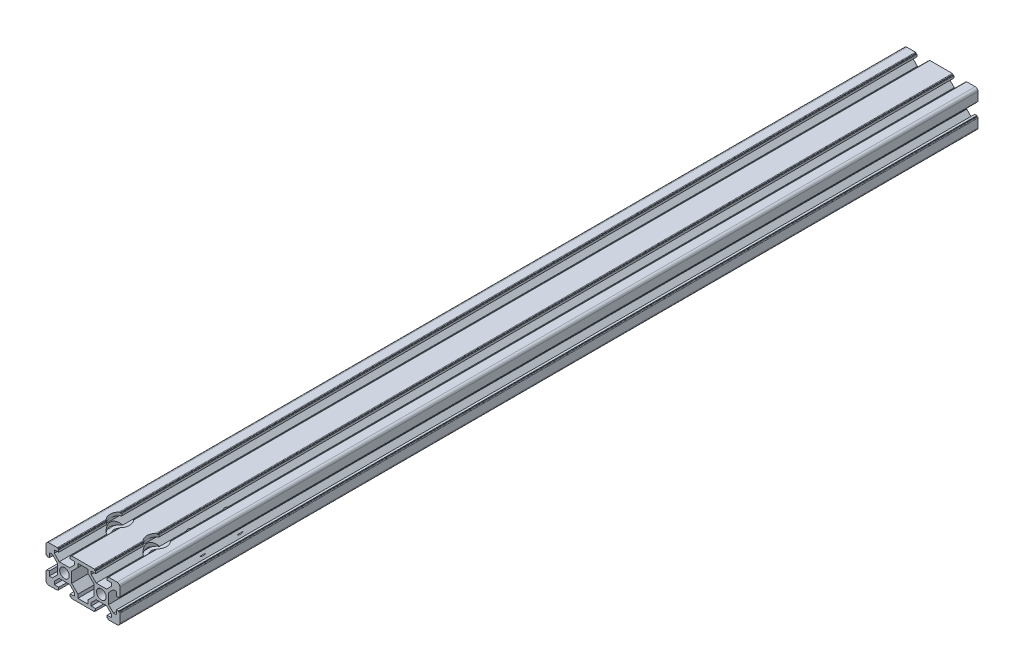
SolidWorks part; units mm, degrees
ref_plane "前视基准面" through (0, 0, 0) normal (0, 0, 1) x (1, 0, 0)
ref_plane "上视基准面" through (0, 0, 0) normal (0, 1, 0) x (1, 0, 0)
ref_plane "右视基准面" through (0, 0, 0) normal (1, 0, 0) x (0, 0, -1)
sketch "草图1" plane through (0, 0, 0) normal (0, 0, 1) x (1, 0, 0)
  line L0 (0, 0) -> (0, -41497.3383) construction
  line L1 (0, 0) -> (41497.3383, 0) construction
  line L2 (-13.9, 0) -> (-13.9, 2.8393)
  line L3 (-13.9, 2.8393) -> (-16.5607, 5.5)
  line L4 (-16.5607, 5.5) -> (-18.2, 5.5)
  line L5 (-18.2, 5.5) -> (-18.2, 3.1)
  line L6 (-18.2, 3.1) -> (-19.4, 3.1)
  line L7 (-19.4, 3.1) -> (-19.4, 3.6)
  line L8 (-19.4, 3.6) -> (-20, 3.6)
  line L9 (-20, 3.6) -> (-20, 10)
  line L10 (-20, 10) -> (-13.6, 10)
  line L11 (-13.6, 10) -> (-13.6, 9.4)
  line L12 (-13.6, 9.4) -> (-13.1, 9.4)
  line L13 (-13.1, 9.4) -> (-13.1, 8.2)
  line L14 (-13.1, 8.2) -> (-15.5, 8.2)
  line L15 (-15.5, 6.5607) -> (-12.8393, 3.9)
  line L16 (-12.8393, 3.9) -> (-7.1607, 3.9)
  line L17 (-4.5, 6.5607) -> (-7.1607, 3.9)
  line L18 (-4.5, 6.5607) -> (-4.5, 8.2)
  line L19 (-4.5, 8.2) -> (-6.9, 8.2)
  line L20 (-6.9, 8.2) -> (-6.9, 9.4)
  line L21 (-6.9, 9.4) -> (-6.4, 9.4)
  line L22 (-6.4, 9.4) -> (-6.4, 10)
  line L23 (-6.4, 10) -> (6.4, 10)
  line L24 (-15.5, 8.2) -> (-15.5, 6.5607)
  line L25 (-10, 0) -> (-20, 10) construction
  line L26 (-6.1, -2.8393) -> (-6.1, 2.8393)
  line L27 (-6.1, 2.8393) -> (-2.7, 6.2393)
  line L28 (-2.7, 6.2393) -> (-2.7, 8.2)
  line L29 (-2.7, 8.2) -> (2.7, 8.2)
  line L30 (-10, 0) -> (0, 10) construction
  line L31 (13.9, 0) -> (13.9, 2.8393)
  line L32 (6.1, -2.8393) -> (6.1, 2.8393)
  line L33 (4.5, 6.5607) -> (7.1607, 3.9)
  line L34 (12.8393, 3.9) -> (7.1607, 3.9)
  line L35 (6.1, 2.8393) -> (2.7, 6.2393)
  line L36 (2.7, 6.2393) -> (2.7, 8.2)
  line L37 (4.5, 6.5607) -> (4.5, 8.2)
  line L38 (6.4, 9.4) -> (6.4, 10)
  line L39 (6.9, 9.4) -> (6.4, 9.4)
  line L40 (6.9, 8.2) -> (6.9, 9.4)
  line L41 (4.5, 8.2) -> (6.9, 8.2)
  line L42 (13.1, 9.4) -> (13.1, 8.2)
  line L43 (13.6, 9.4) -> (13.1, 9.4)
  line L44 (13.6, 10) -> (13.6, 9.4)
  line L45 (20, 10) -> (13.6, 10)
  line L46 (20, 3.6) -> (20, 10)
  line L47 (19.4, 3.6) -> (20, 3.6)
  line L48 (19.4, 3.1) -> (19.4, 3.6)
  line L49 (18.2, 3.1) -> (19.4, 3.1)
  line L50 (18.2, 5.5) -> (18.2, 3.1)
  line L51 (16.5607, 5.5) -> (18.2, 5.5)
  line L52 (13.9, 2.8393) -> (16.5607, 5.5)
  line L53 (15.5, 6.5607) -> (12.8393, 3.9)
  line L54 (15.5, 8.2) -> (15.5, 6.5607)
  line L55 (13.1, 8.2) -> (15.5, 8.2)
  line L56 (15.5, -6.5607) -> (12.8393, -3.9)
  line L57 (13.9, -2.8393) -> (16.5607, -5.5)
  line L58 (16.5607, -5.5) -> (18.2, -5.5)
  line L59 (18.2, -5.5) -> (18.2, -3.1)
  line L60 (18.2, -3.1) -> (19.4, -3.1)
  line L61 (19.4, -3.1) -> (19.4, -3.6)
  line L62 (19.4, -3.6) -> (20, -3.6)
  line L63 (12.8393, -3.9) -> (7.1607, -3.9)
  line L64 (13.9, 0) -> (13.9, -2.8393)
  line L65 (13.1, -8.2) -> (15.5, -8.2)
  line L66 (15.5, -8.2) -> (15.5, -6.5607)
  line L67 (20, -3.6) -> (20, -10)
  line L68 (20, -10) -> (13.6, -10)
  line L69 (13.6, -10) -> (13.6, -9.4)
  line L70 (13.6, -9.4) -> (13.1, -9.4)
  line L71 (13.1, -9.4) -> (13.1, -8.2)
  line L72 (4.5, -8.2) -> (6.9, -8.2)
  line L73 (6.9, -8.2) -> (6.9, -9.4)
  line L74 (6.9, -9.4) -> (6.4, -9.4)
  line L75 (6.4, -9.4) -> (6.4, -10)
  line L76 (4.5, -6.5607) -> (4.5, -8.2)
  line L77 (2.7, -6.2393) -> (2.7, -8.2)
  line L78 (6.1, -2.8393) -> (2.7, -6.2393)
  line L79 (4.5, -6.5607) -> (7.1607, -3.9)
  line L80 (-2.7, -8.2) -> (2.7, -8.2)
  line L81 (-2.7, -6.2393) -> (-2.7, -8.2)
  line L82 (-6.1, -2.8393) -> (-2.7, -6.2393)
  line L83 (-4.5, -6.5607) -> (-7.1607, -3.9)
  line L84 (-4.5, -8.2) -> (-6.9, -8.2)
  line L85 (-4.5, -6.5607) -> (-4.5, -8.2)
  line L86 (-6.4, -10) -> (6.4, -10)
  line L87 (-6.4, -9.4) -> (-6.4, -10)
  line L88 (-6.9, -9.4) -> (-6.4, -9.4)
  line L89 (-6.9, -8.2) -> (-6.9, -9.4)
  line L90 (-13.1, -9.4) -> (-13.1, -8.2)
  line L91 (-13.6, -9.4) -> (-13.1, -9.4)
  line L92 (-13.6, -10) -> (-13.6, -9.4)
  line L93 (-15.5, -8.2) -> (-15.5, -6.5607)
  line L94 (-13.1, -8.2) -> (-15.5, -8.2)
  line L95 (-12.8393, -3.9) -> (-7.1607, -3.9)
  line L96 (-15.5, -6.5607) -> (-12.8393, -3.9)
  line L97 (-13.9, 0) -> (-13.9, -2.8393)
  line L98 (-13.9, -2.8393) -> (-16.5607, -5.5)
  line L99 (-19.4, -3.6) -> (-20, -3.6)
  line L100 (-19.4, -3.1) -> (-19.4, -3.6)
  line L101 (-18.2, -3.1) -> (-19.4, -3.1)
  line L102 (-18.2, -5.5) -> (-18.2, -3.1)
  line L103 (-16.5607, -5.5) -> (-18.2, -5.5)
  line L104 (-20, -3.6) -> (-20, -10)
  line L105 (-20, -10) -> (-13.6, -10)
  circle A0 centre (-10, 0) radius 2.6
  circle A1 centre (10, 0) radius 2.6
  point P50 (0, 8.2)
  point P95 (6.1, 0)
  point P96 (-6.1, 0)
  dimension "D1" = 5.2
  dimension "D2" = 45
  dimension "D3" = 1.5
  dimension "D4" = 20
  dimension "D5" = 40
  dimension "D6" = 0.75
  dimension "D7" = 7.2
  dimension "D8" = 6.2
  dimension "D9" = 6.1
  dimension "D10" = 1.8
  dimension "D11" = 1.2
  dimension "D12" = 12.2
  dimension "D13" = 5.4
  dimension "D14" = 11
  dimension "D15" = 1.5
  dimension "D16" = 0.75
extrude "凸台-拉伸1" add sketch "草图1" along normal mid plane 465
fillet "圆角1" radius 1.5 4 edges at (20, -10, 0) (20, 10, 0) (-20, -10, 0) (-20, 10, 0)
fillet "圆角2" radius 0.3 12 edges at (-6.4, 10, 0) (-13.6, 10, 0) (-20, 3.6, 0) (-20, -3.6, 0) (-13.6, -10, 0) (-6.4, -10, 0) (6.4, -10, 0) (20, -3.6, 0) (20, 3.6, 0) (13.6, -10, 0) (13.6, 10, 0) (6.4, 10, 0)
sketch "草图2" plane through (0, -3.9, 0) normal (0, -1, 0) x (1, 0, 0)
  line L0 (10, 202.5) -> (-10, 202.5) construction
  circle A0 centre (-10, 202.5) radius 3.1
  circle A1 centre (10, 202.5) radius 3.1
  point P3 (0, 202.5)
  dimension "D2" = 30
  dimension "D3" = 6.2
  dimension "D1" = 20
extrude "切除-拉伸1" cut sketch "草图2" against normal through all both and the other way through all
sketch "草图3" plane through (0, 3.9, 0) normal (0, 1, 0) x (1, 0, 0)
  circle A0 centre (-10, -202.5) radius 5.25
  circle A1 centre (10, -202.5) radius 5.25
  dimension "D1" = 10.5
extrude "切除-拉伸2" cut sketch "草图3" along normal through all
sketch "草图4" plane through (0, 3.9, 0) normal (0, 1, 0) x (1, 0, 0)
  line L0 (10, -162.5) -> (10, -182.5) construction
  line L1 (20, 232.5) -> (20, -232.5) construction
  circle A0 centre (10, -182.5) radius 3.1
  circle A1 centre (10, -162.5) radius 3.1
  circle A2 centre (10, -202.5) radius 3.1 construction
  dimension "D1" = 20
  dimension "D2" = 20
  dimension "D3" = 6.2
  dimension "D4" = 10
extrude "切除-拉伸3" cut sketch "草图4" against normal through all both and the other way through all
sketch "草图6" plane through (0, -3.9, 0) normal (0, -1, 0) x (1, 0, 0)
  circle A0 centre (10, 182.5) radius 5.25
  circle A1 centre (10, 162.5) radius 5.25
  dimension "D1" = 10.5
extrude "切除-拉伸4" cut sketch "草图6" along normal through all
equation "\"D6@草图1\"=1/2*\"D3@草图1\""
equation "\"D16@草图1\"=0.5*\"D15@草图1\""
